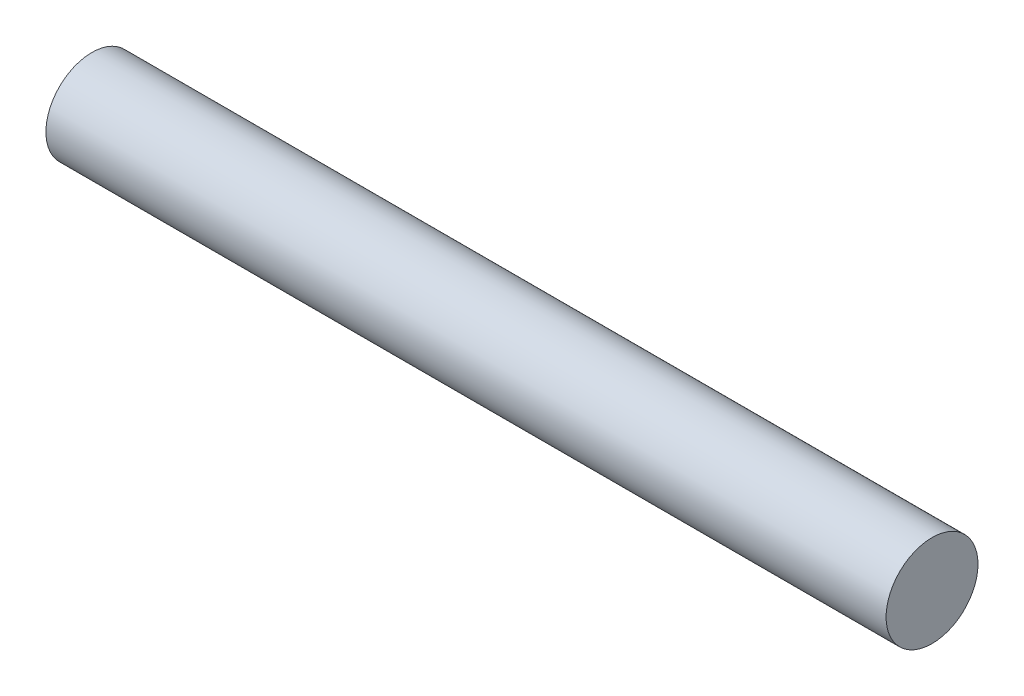
SolidWorks part; units mm, degrees
ref_plane "Front Plane" through (0, 0, 0) normal (0, 0, 1) x (1, 0, 0)
ref_plane "Top Plane" through (0, 0, 0) normal (0, 1, 0) x (1, 0, 0)
ref_plane "Right Plane" through (0, 0, 0) normal (1, 0, 0) x (0, 0, -1)
sketch "Sketch1" plane through (0, 0, 0) normal (0, 0, 1) x (1, 0, 0)
  line L0 (0, 0) -> (203.2, 0)
  line L1 (48.0728, 0) -> (-48.0728, 0) construction
  point P5 (158.75, 0)
  point P8 (44.45, 0)
  dimension "D1" = 158.75
  dimension "D2" = 44.45
  dimension "D3" = 44.45
sweep "Sweep1" add path "Sketch1" circular profile diameter 22.225 parameters "D3"=22.225
sketch "Sketch18" plane through (0, 0, 0) normal (0, 0, 1) x (1, 0, 0)
  circle A0 centre (44.45, 0) radius 3.175
  dimension "D1" = 6.35
extrude "Cut-Extrude1" cut sketch "Sketch18" against normal through all contours A0
equation "\"bar_dia\"= 0.875"
equation "\"D3@Sweep1\"=\"bar_dia\""
equation "\"hole_dia\"= 0.25in"
equation "\"D1@Sketch18\"=\"hole_dia\" "
